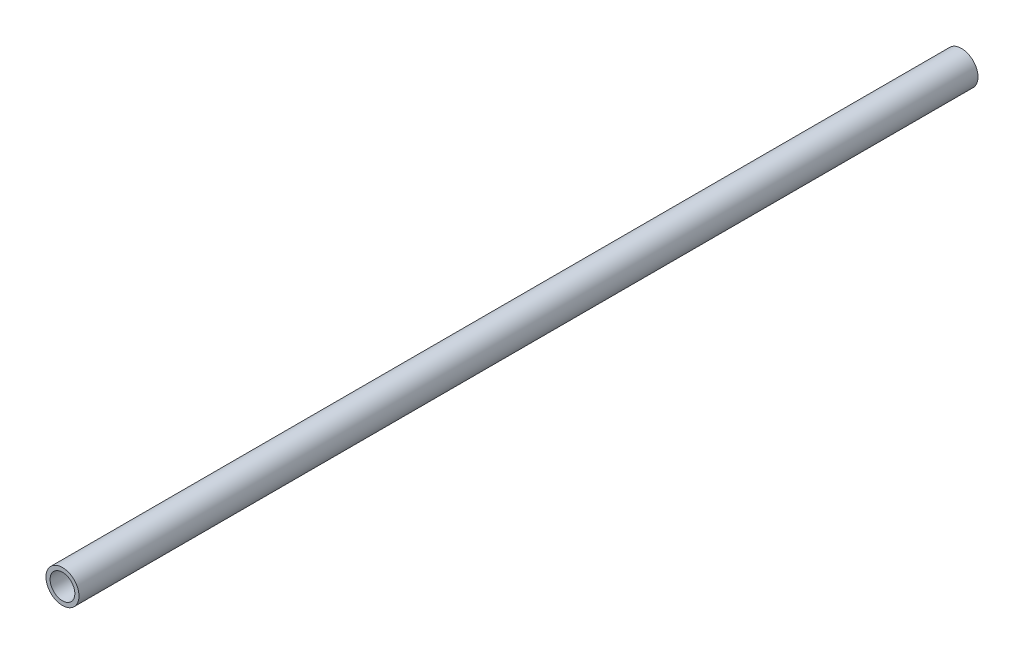
SolidWorks part; units mm, degrees
material "Alliage 1060"
ref_plane "Front" through (0, 0, 0) normal (0, 0, 1) x (1, 0, 0)
ref_plane "Top" through (0, 0, 0) normal (0, 1, 0) x (1, 0, 0)
ref_plane "Right" through (0, 0, 0) normal (1, 0, 0) x (0, 0, -1)
sketch "Esquisse1" plane through (0, 0, 0) normal (0, 0, 1) x (1, 0, 0)
  circle A0 centre (0, 0) radius 4
  dimension "D1" = 8
extrude "Extru.-Mince1" add sketch "Esquisse1" along normal blind 218 thin thin type one direction reverse wall 1
